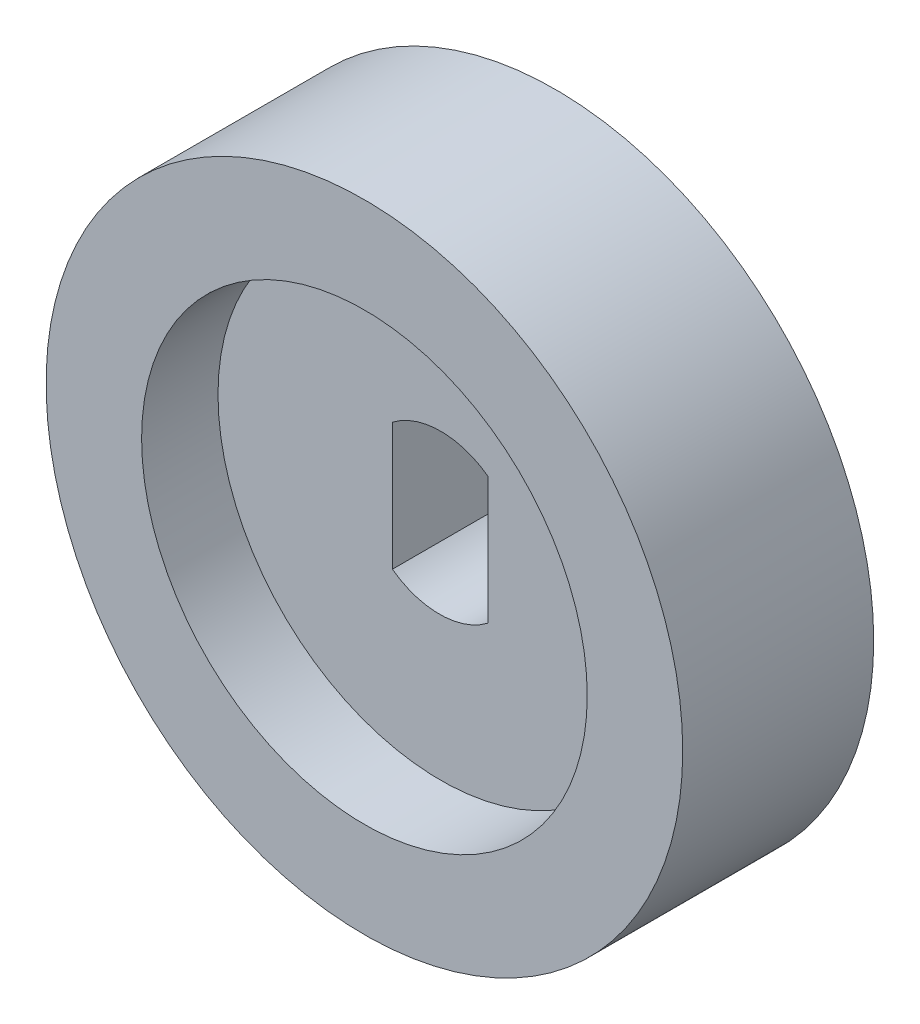
SolidWorks part; units mm, degrees
ref_plane "Front Plane" through (0, 0, 0) normal (0, 0, 1) x (1, 0, 0)
ref_plane "Top Plane" through (0, 0, 0) normal (0, 1, 0) x (1, 0, 0)
ref_plane "Right Plane" through (0, 0, 0) normal (1, 0, 0) x (0, 0, -1)
sketch "Sketch1" plane through (0, 0, 0) normal (0, 0, 1) x (1, 0, 0)
  line L0 (-1.5216, 1.9836) -> (-1.5216, -2.0164)
  line L1 (1.4783, 2.0161) -> (1.4783, -1.9839)
  circle A0 centre (0, 0) radius 10
  arc A2 (-1.5216, 1.9836) -> (1.4783, 2.0161) centre (0, 0) cw
  arc A3 (-1.5216, -2.0164) -> (1.4783, -1.9839) centre (-0.0433, -0.0002) ccw
  point P9 (0, 0)
extrude "Boss-Extrude1" add sketch "Sketch1" along normal mid plane 6
sketch "Sketch2" plane through (0, 0, 3) normal (0, 0, 1) x (1, 0, 0)
  circle A0 centre (0, 0) radius 7
  dimension "D1" = 14
extrude "Cut-Extrude1" cut sketch "Sketch2" against normal blind 2.4
